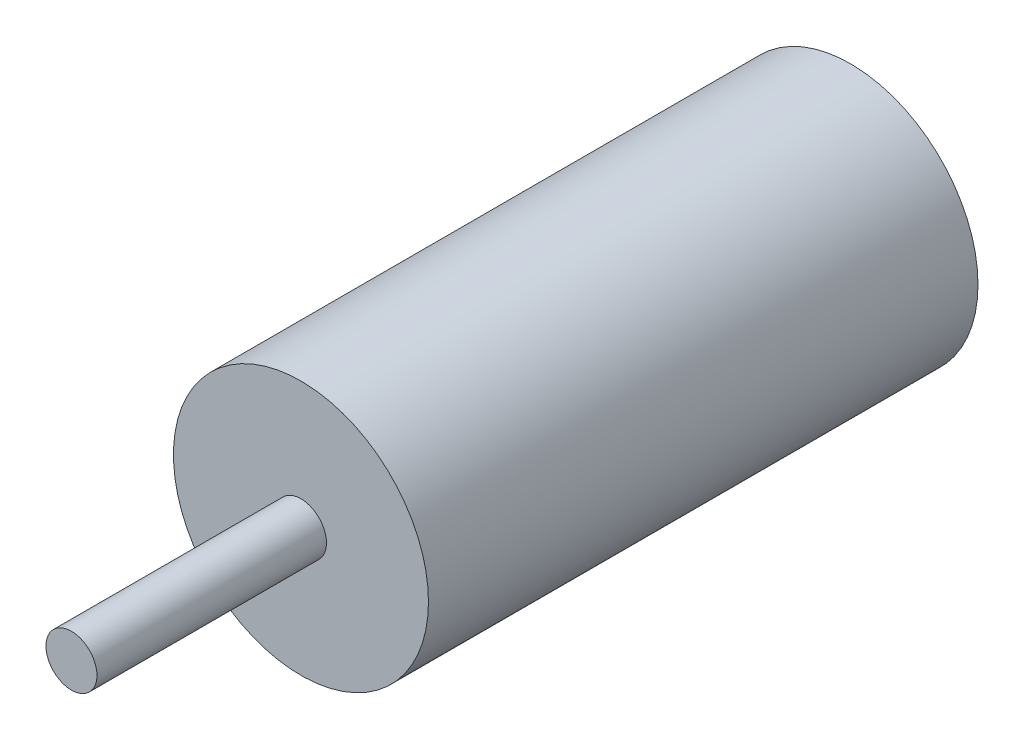
SolidWorks part; units mm, degrees
ref_plane "Front Plane" through (0, 0, 0) normal (0, 0, 1) x (1, 0, 0)
ref_plane "Top Plane" through (0, 0, 0) normal (0, 1, 0) x (1, 0, 0)
ref_plane "Right Plane" through (0, 0, 0) normal (1, 0, 0) x (0, 0, -1)
sketch "Sketch2" plane through (0, 0, 0) normal (0, 0, 1) x (1, 0, 0)
  circle A0 centre (0, 0) radius 10
  dimension "D1" = 20
extrude "Boss-Extrude1" add sketch "Sketch2" along normal blind 43.1
sketch "Sketch3" plane through (0, 0, 43.1) normal (0, 0, 1) x (1, 0, 0)
  circle A0 centre (0, 0) radius 2
  dimension "D1" = 4
extrude "Boss-Extrude2" add sketch "Sketch3" along normal offset from surface (18 mm away) 61.1 up to face at (10, 0, 0)
